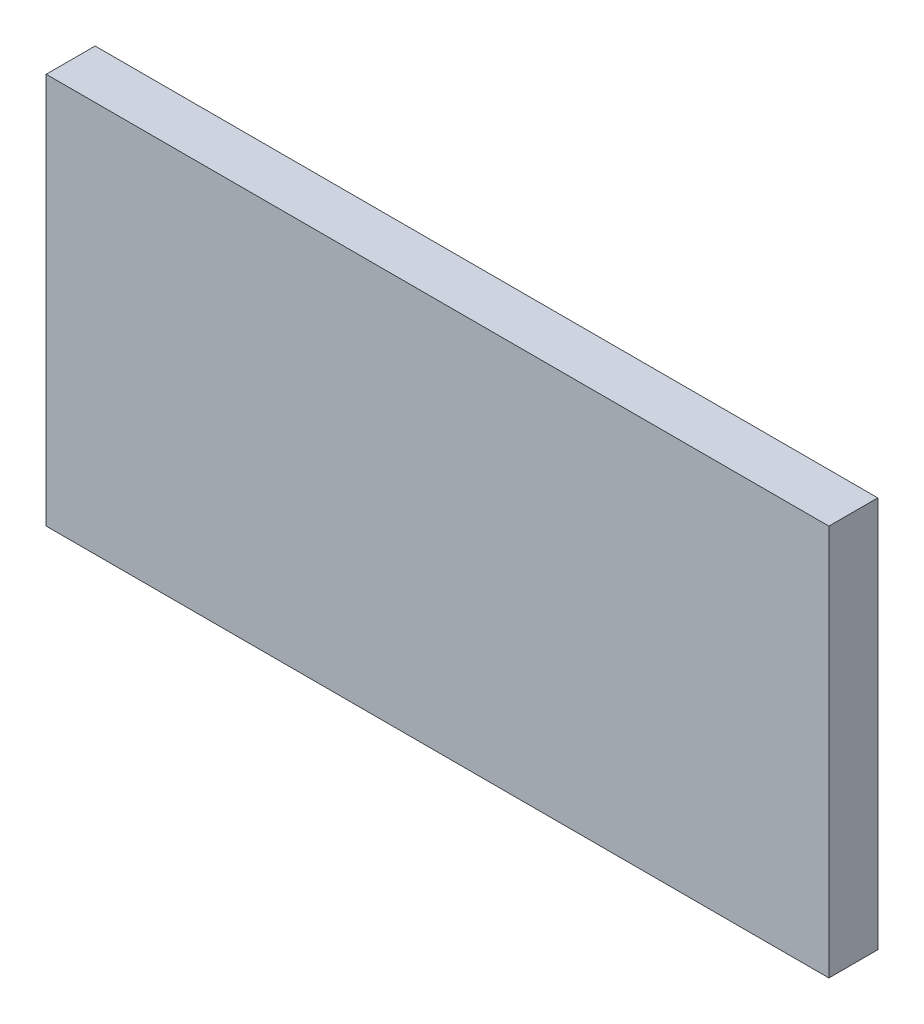
SolidWorks part; units mm, degrees
material "Cast Carbon Steel"
ref_plane "Front Plane" through (0, 0, 0) normal (0, 0, 1) x (1, 0, 0)
ref_plane "Top Plane" through (0, 0, 0) normal (0, 1, 0) x (1, 0, 0)
ref_plane "Right Plane" through (0, 0, 0) normal (1, 0, 0) x (0, 0, -1)
sketch "Sketch1" plane through (0, 0, 0) normal (0, 0, 1) x (1, 0, 0)
  line L0 (0, 87.15) -> (0, 99.85) construction
  line L1 (12.7, 87.15) -> (-12.7, 87.15) construction
  line L2 (-12.7, 99.85) -> (12.7, 99.85) construction
  line L4 (-12.7, 87.15) -> (12.7, 87.15)
  line L5 (-12.7, 87.15) -> (-12.7, 99.85)
  line L6 (-12.7, 99.85) -> (12.7, 99.85)
  line L7 (12.7, 87.15) -> (12.7, 99.85)
  line L8 (-12.7, 87.15) -> (12.7, 99.85) construction
  line L9 (-12.7, 99.85) -> (12.7, 87.15) construction
  point P6 (0, 93.5)
  dimension "D1" = 25.4
  dimension "D2" = 12.7
extrude "Boss-Extrude1" add sketch "Sketch1" along normal blind 1.5875
